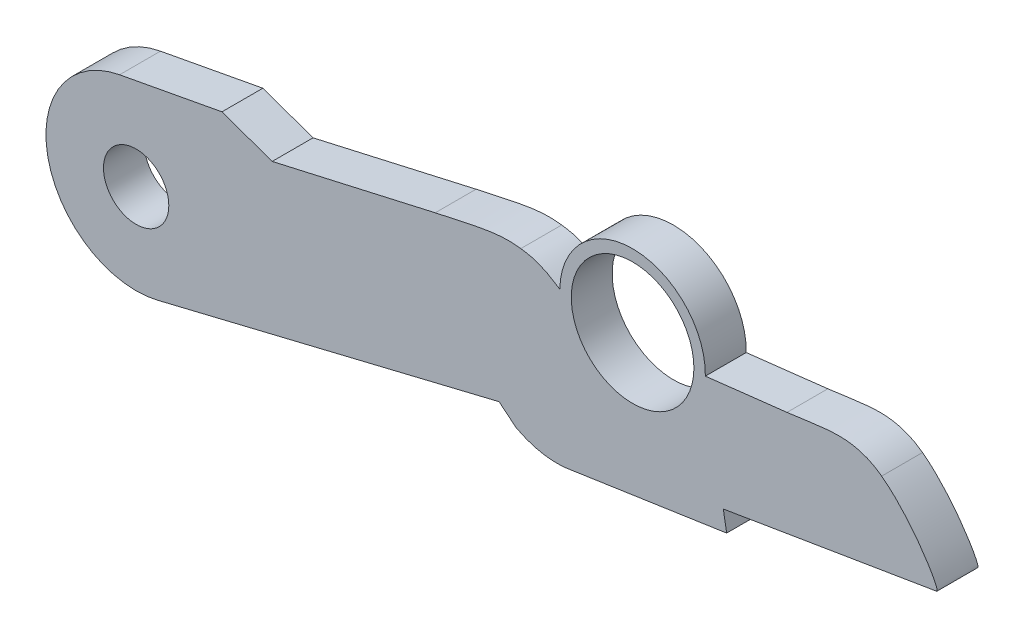
SolidWorks part; units mm, degrees
ref_plane "Front Plane" through (0, 0, 0) normal (0, 0, 1) x (1, 0, 0)
ref_plane "Top Plane" through (0, 0, 0) normal (0, 1, 0) x (1, 0, 0)
ref_plane "Right Plane" through (0, 0, 0) normal (1, 0, 0) x (0, 0, -1)
sketch "Sketch1" plane through (0, 0, 0) normal (0, 0, 1) x (1, 0, 0)
  line L0 (-185.2159, 133.9473) -> (-185.2137, 133.9472)
  line L1 (-185.2137, 133.9472) -> (-181.2226, 134.4074)
  line L2 (-173.9005, 130.4901) -> (-184.3369, 128.7571)
  line L3 (-184.3369, 128.7571) -> (-184.1731, 127.8179)
  line L4 (-184.1731, 127.8179) -> (-192.0168, 126.6512)
  line L5 (-194.4669, 127.1276) -> (-195.3066, 127.8179)
  line L11 (-208.8639, 133.3225) -> (-206.4085, 132.4481)
  line L12 (-206.4085, 132.4481) -> (-198.431, 134.2606)
  line L16 (-208.8639, 133.3225) -> (-213.8742, 132.3869)
  line L17 (-195.3066, 127.8179) -> (-212.0239, 123.7615)
  circle A0 centre (-213.0643, 128.0495) radius 1.5984
  arc A6 (-185.2159, 133.9473) -> (-192.3352, 134.072) centre (-188.7755, 134.0096) ccw
  circle A7 centre (-188.7755, 134.0096) radius 3
  arc A10 (-213.8742, 132.3869) -> (-212.0239, 123.7615) centre (-213.0643, 128.0495) ccw
  spline S5 degree 3 poles (-181.2226, 134.4074) (-179.4701, 134.6094) (-178.0074, 135.082) (-176.5896, 134.0235) knots 0.1 0.1 0.1 0.1 0.133333 0.133333 0.133333 0.133333
  spline S6 degree 3 poles (-176.5896, 134.0235) (-175.0534, 132.8767) (-173.6744, 130.5277) (-173.9005, 130.4901) knots 0.133333 0.133333 0.133333 0.133333 0.166667 0.166667 0.166667 0.166667
  spline S7 degree 3 poles (-192.0168, 126.6512) (-192.908, 126.5527) (-193.7163, 126.7396) (-194.4669, 127.1276) knots 0.266667 0.266667 0.266667 0.266667 0.3 0.3 0.3 0.3
  spline S12 degree 3 poles (-198.431, 134.2606) (-196.4166, 134.6847) (-195.3222, 134.9962) (-194.245, 134.8359) knots 0.833333 0.833333 0.833333 0.833333 0.866667 0.866667 0.866667 0.866667
  spline S13 degree 3 poles (-194.245, 134.8359) (-193.6661, 134.7498) (-193.2835, 134.6919) (-192.3352, 134.072) knots 0.866667 0.866667 0.866667 0.866667 0.9 0.9 0.9 0.9
  point P15 (-195.3066, 127.8179)
  dimension "D2" = 6
extrude "Boss-Extrude1" add sketch "Sketch1" along normal blind 2
scale "Scale1" scale about centroid uniform scaling yes scale factor 2.8
